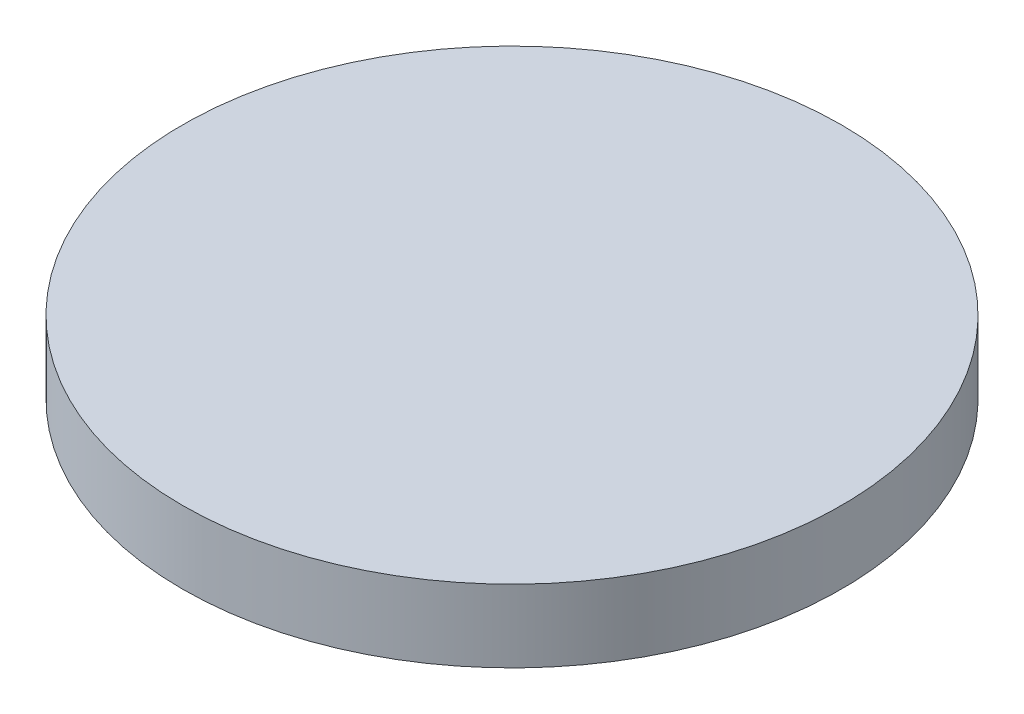
SolidWorks part; units mm, degrees
ref_plane "Front Plane" through (0, 0, 0) normal (0, 0, 1) x (1, 0, 0)
ref_plane "Top Plane" through (0, 0, 0) normal (0, 1, 0) x (1, 0, 0)
ref_plane "Right Plane" through (0, 0, 0) normal (1, 0, 0) x (0, 0, -1)
sketch "Sketch1" plane through (0, 0, 0) normal (0, 1, 0) x (1, 0, 0)
  circle A0 centre (0, 0) radius 20
  dimension "D1" = 40
extrude "Boss-Extrude1" add sketch "Sketch1" along normal blind 4.4
